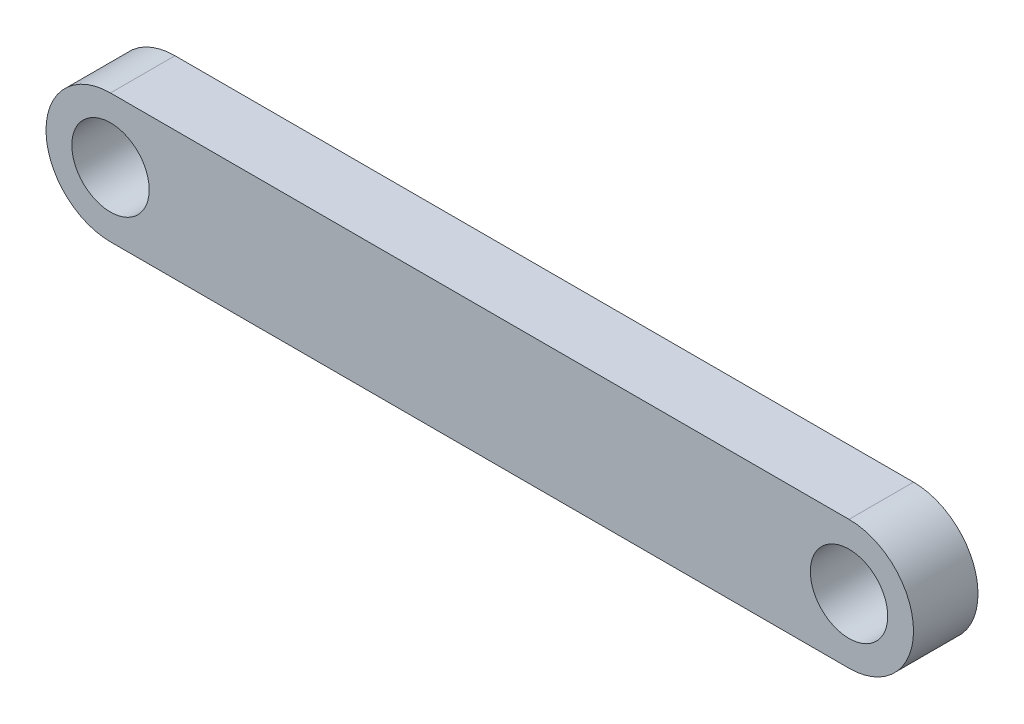
SolidWorks part; units mm, degrees
material "6061-T6 (SS)"
ref_plane "前视基准面" through (0, 0, 0) normal (0, 0, 1) x (1, 0, 0)
ref_plane "上视基准面" through (0, 0, 0) normal (0, 1, 0) x (1, 0, 0)
ref_plane "右视基准面" through (0, 0, 0) normal (1, 0, 0) x (0, 0, -1)
sketch "草图2" plane through (0, 0, 0) normal (0, 0, 1) x (1, 0, 0)
  line L0 (0, 0) -> (572.6, 0) construction
  line L1 (0, 50) -> (572.6, 50)
  line L2 (0, -50) -> (572.6, -50)
  arc A0 (0, 50) -> (0, -50) centre (0, 0) ccw
  arc A1 (572.6, -50) -> (572.6, 50) centre (572.6, 0) ccw
  circle A2 centre (0, 0) radius 30
  circle A3 centre (572.6, 0) radius 30
  point P3 (286.3, 0)
  dimension "D1" = 60
  dimension "D2" = 100
  dimension "Linklength" = 572.6
extrude "凸台-拉伸1" add sketch "草图2" along normal blind 50
sketch "草图3" [suppressed] plane through (0, 0, 50) normal (0, 0, 1) x (1, 0, 0)
  circle A0 centre (980, 0) radius 30
  circle A1 centre (0, 0) radius 30 construction
  dimension "D1" = 980
extrude "切除-拉伸1" [suppressed] cut sketch "草图3" against normal blind 381
sketch "草图4" [suppressed] plane through (0, 0, 50) normal (0, 0, 1) x (1, 0, 0)
  circle A0 centre (2584.1, 0) radius 30
  circle A1 centre (0, 0) radius 30 construction
  dimension "D1" = 2584.1
extrude "切除-拉伸2" [suppressed] cut sketch "草图4" against normal blind 381
